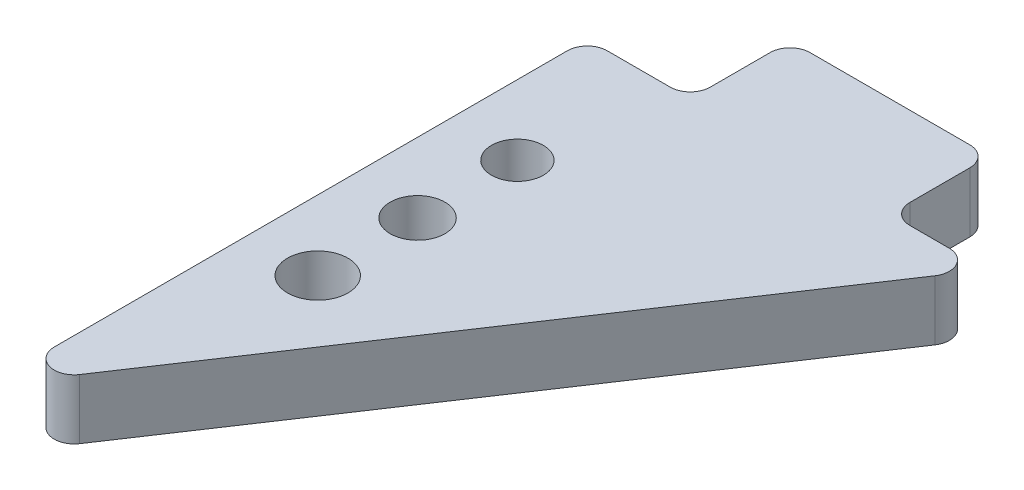
SolidWorks part; units mm, degrees
material "aplakash"
ref_plane "Front Plane" through (0, 0, 0) normal (0, 0, 1) x (1, 0, 0)
ref_plane "Top Plane" through (0, 0, 0) normal (0, 1, 0) x (1, 0, 0)
ref_plane "Right Plane" through (0, 0, 0) normal (1, 0, 0) x (0, 0, -1)
sketch "Sketch1" plane through (0, 0, 0) normal (0, 1, 0) x (1, 0, 0)
  line L0 (46.4435, -40.2582) -> (63.575, -14.561)
  line L1 (45.6114, -13.0063) -> (48.7678, -13.0063)
  line L2 (44.6114, -14.0063) -> (44.6114, -39.7035)
  line L5 (60.7678, -13.0063) -> (62.7429, -13.0063)
  line L7 (49.7678, -12.0063) -> (49.7678, -9.0063)
  line L8 (50.7678, -8.0063) -> (58.7678, -8.0063)
  line L9 (59.7678, -12.0063) -> (59.7678, -9.0063)
  arc A0 (49.7678, -9.0063) -> (50.7678, -8.0063) centre (50.7678, -9.0063) cw
  arc A1 (58.7678, -8.0063) -> (59.7678, -9.0063) centre (58.7678, -9.0063) cw
  arc A2 (60.7678, -13.0063) -> (59.7678, -12.0063) centre (60.7678, -12.0063) cw
  arc A3 (48.7678, -13.0063) -> (49.7678, -12.0063) centre (48.7678, -12.0063) ccw
  arc A4 (45.6114, -13.0063) -> (44.6114, -14.0063) centre (45.6114, -14.0063) ccw
  arc A5 (44.6114, -39.7035) -> (46.4435, -40.2582) centre (45.6114, -39.7035) ccw
  arc A6 (62.7429, -13.0063) -> (63.575, -14.561) centre (62.7429, -14.0063) cw
  circle A7 centre (48.1114, -30.0063) radius 1.5135
  circle A8 centre (48.1114, -25.0063) radius 1.3715
  circle A9 centre (48.1114, -20.0063) radius 1.2995
  point P8 (54.7678, -8.0063)
  point P10 (49.7678, -8.0063)
  point P13 (59.7678, -8.0063)
  point P16 (59.7678, -13.0063)
  point P21 (44.6114, -13.0063)
  point P24 (44.6114, -43.0063)
  point P27 (64.6114, -13.0063)
  point P34 (0, 0)
  point P35 (48.4053, -18.8185)
  point P36 (0, 0)
  point P37 (47.7457, -17.7213)
  point P38 (48.1114, -29.7904)
  dimension "D5" = 1
  dimension "D1" = 30
  dimension "D2" = 20
  dimension "D3" = 10
  dimension "D4" = 5
  dimension "D6" = 5
  dimension "D7" = 5
  dimension "D8" = 7
  dimension "D9" = 3.5
extrude "Boss-Extrude1" add sketch "Sketch1" along normal blind 3
